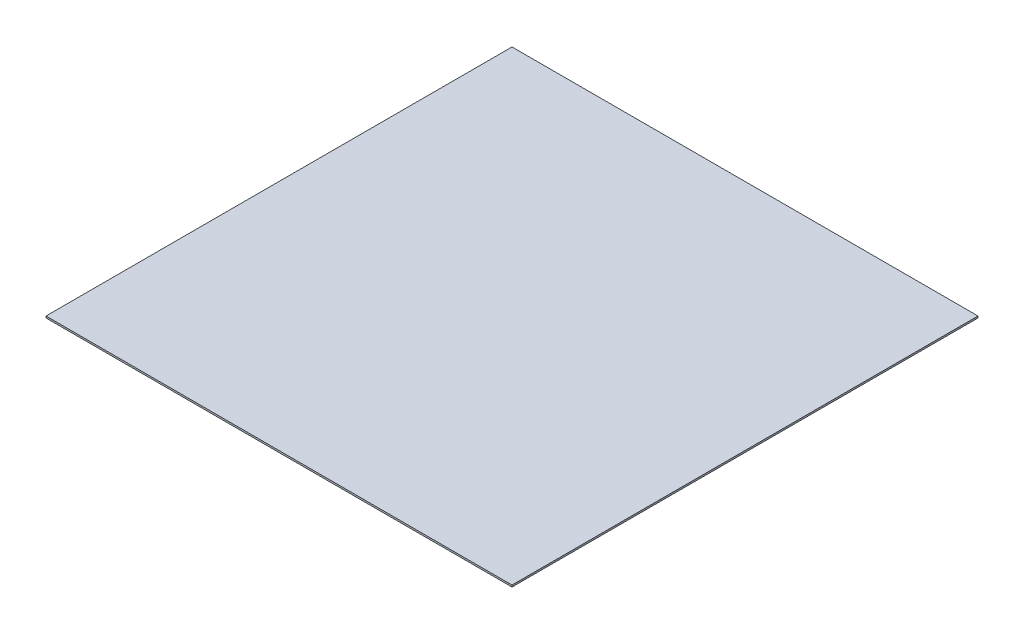
SolidWorks part; units mm, degrees
material "红木"
ref_plane "前视基准面" through (0, 0, 0) normal (0, 0, 1) x (1, 0, 0)
ref_plane "上视基准面" through (0, 0, 0) normal (0, 1, 0) x (1, 0, 0)
ref_plane "右视基准面" through (0, 0, 0) normal (1, 0, 0) x (0, 0, -1)
sketch "草图1" plane through (0, 0, 0) normal (0, 1, 0) x (1, 0, 0)
  line L1 (-400, -400) -> (400, -400)
  line L2 (-400, -400) -> (-400, 400)
  line L3 (-400, 400) -> (400, 400)
  line L4 (400, -400) -> (400, 400)
  line L5 (-400, -400) -> (400, 400) construction
  line L6 (-400, 400) -> (400, -400) construction
  point P0 (0, 0)
  dimension "D1" = 800
  dimension "D2" = 800
extrude "凸台-拉伸1" add sketch "草图1" along normal blind 3
